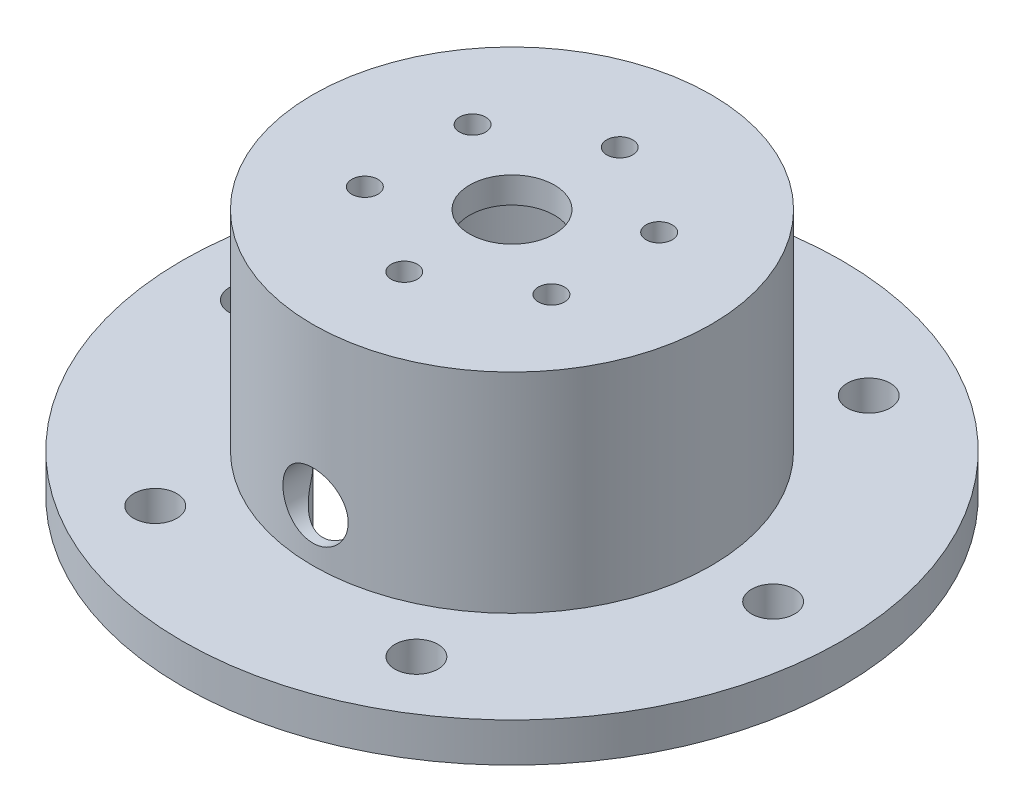
SolidWorks part; units mm, degrees
ref_plane "Front Plane" through (0, 0, 0) normal (0, 0, 1) x (1, 0, 0)
ref_plane "Top Plane" through (0, 0, 0) normal (0, 1, 0) x (1, 0, 0)
ref_plane "Right Plane" through (0, 0, 0) normal (1, 0, 0) x (0, 0, -1)
sketch "Sketch1" plane through (0, 0, 0) normal (0, 0, 1) x (1, 0, 0)
  line L0 (0, -8.7813) -> (0, 7.1563) construction
  line L1 (3.25, 8.5) -> (3.25, 10.5)
  line L2 (3.25, 10.5) -> (15.25, 10.5)
  line L3 (15.25, 10.5) -> (15.25, -5.5)
  line L4 (15.25, -5.5) -> (25.25, -5.5)
  line L5 (25.25, -5.5) -> (25.25, -8.5)
  line L6 (25.25, -8.5) -> (13, -8.5)
  line L7 (13, -8.5) -> (13, 8.5)
  line L8 (13, 8.5) -> (3.25, 8.5)
  point P5 (13, 0)
  dimension "D1" = 2
  dimension "D2" = 30.5
  dimension "D3" = 3
  dimension "D4" = 6.5
  dimension "D5" = 26
  dimension "D6" = 17
  dimension "D7" = 10
revolve "Revolve1" add sketch "Sketch1" angle 360 about L0
sketch "Sketch2" plane through (0, 10.5, 0) normal (0, 1, 0) x (1, 0, 0)
  line L0 (-6.118, 0) -> (7.121, 0) construction
  circle A0 centre (0, 8.25) radius 1
  circle A1 centre (20, 0) radius 1.65
  dimension "D2" = 2
  dimension "D3" = 3.3
  dimension "D1" = 16.5
  dimension "D4" = 20
extrude "Cut-Extrude1" cut sketch "Sketch2" against normal through all
pattern_circular "CirPattern1" count 6 over 360 about axis through (0, 0, 0) along (0, 1, 0) of "Cut-Extrude1"
sketch "Sketch3" plane through (0, 0, 0) normal (0, 0, 1) x (1, 0, 0)
  line L0 (-13, 8.5) -> (13, 8.5) construction
  circle A0 centre (0, -1.5) radius 2.5
  dimension "D2" = 5
  dimension "D1" = 10
extrude "Cut-Extrude2" cut sketch "Sketch3" along normal through all
sketch "Sketch4" plane through (0, -8.5, 0) normal (0, -1, 0) x (1, 0, 0)
  arc A0 (2.5, 12.7574) -> (-2.5, 12.7574) centre (0, 0) ccw construction
  arc A1 (2.5, 12.7574) -> (-2.5, 12.7574) centre (0, 0) ccw
  arc A2 (2.5, 12.7574) -> (-2.5, 12.7574) centre (0, 11.8354) ccw
  point P4 (0, 14.5)
  point P5 (0, 13)
  dimension "D1" = 1.5
extrude "Cut-Extrude3" cut sketch "Sketch4" against normal blind 10
